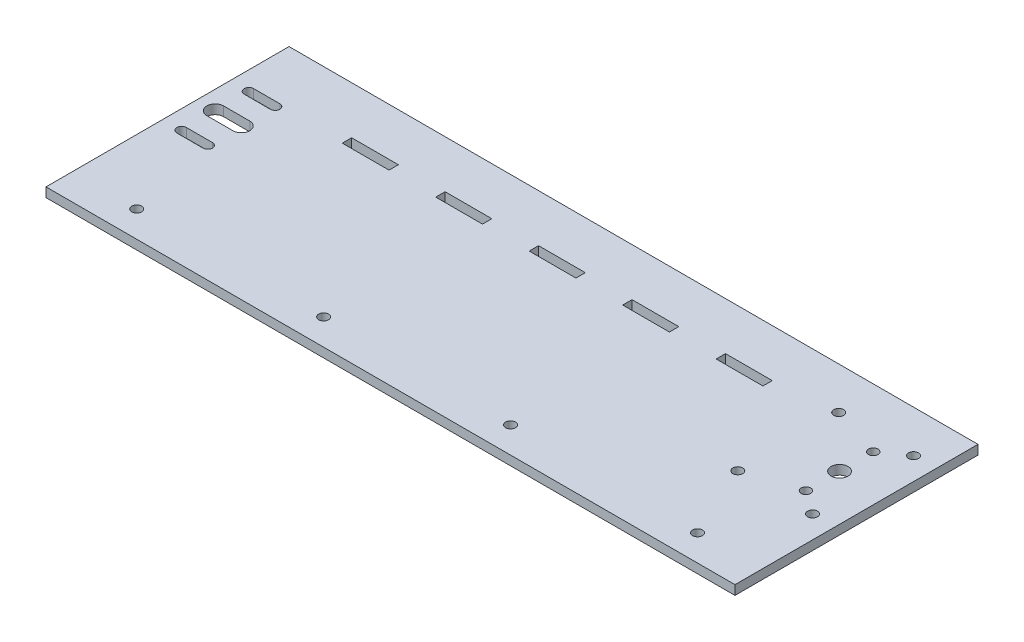
SolidWorks part; units mm, degrees
ref_plane "Front Plane" through (0, 0, 0) normal (0, 0, 1) x (1, 0, 0)
ref_plane "Top Plane" through (0, 0, 0) normal (0, 1, 0) x (1, 0, 0)
ref_plane "Right Plane" through (0, 0, 0) normal (1, 0, 0) x (0, 0, -1)
sketch "Sketch1" plane through (0, 0, 0) normal (0, 1, 0) x (1, 0, 0)
  line L0 (0, 0) -> (0, 40)
  line L3 (0, 40) -> (0, 65)
  line L5 (0, 0) -> (0, -65)
  line L11 (-358.537, 20) -> (-344.537, 20)
  line L12 (-344.5, 0.05) -> (-358.5, 0.05)
  line L15 (-309.5556, 39.5) -> (-284.5556, 39.5)
  line L17 (-344.5, -5.05) -> (-358.5, -5.05)
  line L19 (-259.5556, 39.5) -> (-234.5556, 39.5)
  line L21 (-358.537, 11) -> (-344.537, 11)
  line L22 (0, 65) -> (-368.537, 65)
  line L23 (-358.5, 36.05) -> (-344.5, 36.05)
  line L25 (-358.5, 30.95) -> (-344.5, 30.95)
  line L28 (-309.5556, 39.5) -> (-309.5556, 34.5)
  line L29 (-309.5556, 34.5) -> (-284.5556, 34.5)
  line L30 (-284.5556, 34.5) -> (-284.5556, 39.5)
  line L31 (-209.5556, 39.5) -> (-184.5556, 39.5)
  line L32 (-259.5556, 39.5) -> (-259.5556, 34.5)
  line L33 (-259.5556, 34.5) -> (-234.5556, 34.5)
  line L34 (-234.5556, 34.5) -> (-234.5556, 39.5)
  line L35 (-159.5556, 39.5) -> (-134.5556, 39.5)
  line L36 (-209.5556, 39.5) -> (-209.5556, 34.5)
  line L37 (-209.5556, 34.5) -> (-184.5556, 34.5)
  line L38 (-184.5556, 34.5) -> (-184.5556, 39.5)
  line L41 (-368.537, 65) -> (-368.537, -65)
  line L42 (-109.5556, 39.5) -> (-84.5556, 39.5)
  line L43 (-159.5556, 39.5) -> (-159.5556, 34.5)
  line L44 (-159.5556, 34.5) -> (-134.5556, 34.5)
  line L45 (-134.5556, 34.5) -> (-134.5556, 39.5)
  line L46 (-368.537, -65) -> (0, -65)
  line L47 (-109.5556, 39.5) -> (-109.5556, 34.5)
  line L48 (-109.5556, 34.5) -> (-84.5556, 34.5)
  line L49 (-84.5556, 34.5) -> (-84.5556, 39.5)
  circle A0 centre (-12, 42.5) radius 2.65
  circle A1 centre (-24.537, 33.5) radius 2.55
  circle A2 centre (-24.537, -2.5) radius 2.55
  circle A3 centre (-24.537, 15.5) radius 4.5
  circle A5 centre (-12, -11.5) radius 2.65
  circle A7 centre (-334.037, -51) radius 2.65
  circle A8 centre (-234.037, -51) radius 2.65
  circle A9 centre (-134.037, -51) radius 2.65
  circle A10 centre (-34.037, -51) radius 2.65
  circle A15 centre (-52, -11.5) radius 2.65
  circle A16 centre (-52, 42.5) radius 2.65
  arc A18 (-344.5, 30.95) -> (-344.5, 36.05) centre (-344.5, 33.5) ccw
  arc A19 (-344.5, -5.05) -> (-344.5, 0.05) centre (-344.5, -2.5) ccw
  arc A20 (-344.537, 11) -> (-344.537, 20) centre (-344.537, 15.5) ccw
  arc A22 (-358.537, 20) -> (-358.537, 11) centre (-358.537, 15.5) ccw
  arc A23 (-358.5, 0.05) -> (-358.5, -5.05) centre (-358.5, -2.5) ccw
  arc A24 (-358.5, 36.05) -> (-358.5, 30.95) centre (-358.5, 33.5) ccw
  dimension "D4" = 18
  dimension "D8" = 5.1
  dimension "D9" = 5.1
  dimension "D13" = 65
  dimension "D19" = 368.537
  dimension "D20" = 25
  dimension "D21" = 5
  dimension "D24" = 5
  dimension "D25" = 25
  dimension "D26" = 25
  dimension "D30" = 40
  dimension "D14" = 5.3
  dimension "D28" = 25
  dimension "D15" = 18
  dimension "D35" = 5.3
  dimension "D10" = 25
  dimension "D11" = 40
  dimension "D22" = 25
  dimension "D23" = 25
  dimension "D27" = 25
  dimension "D29" = 25
  dimension "D31" = 25
  dimension "D39" = 100
  dimension "D40" = 100
  dimension "D41" = 100
extrude "Boss-Extrude1" add sketch "Sketch1" along normal blind 5
